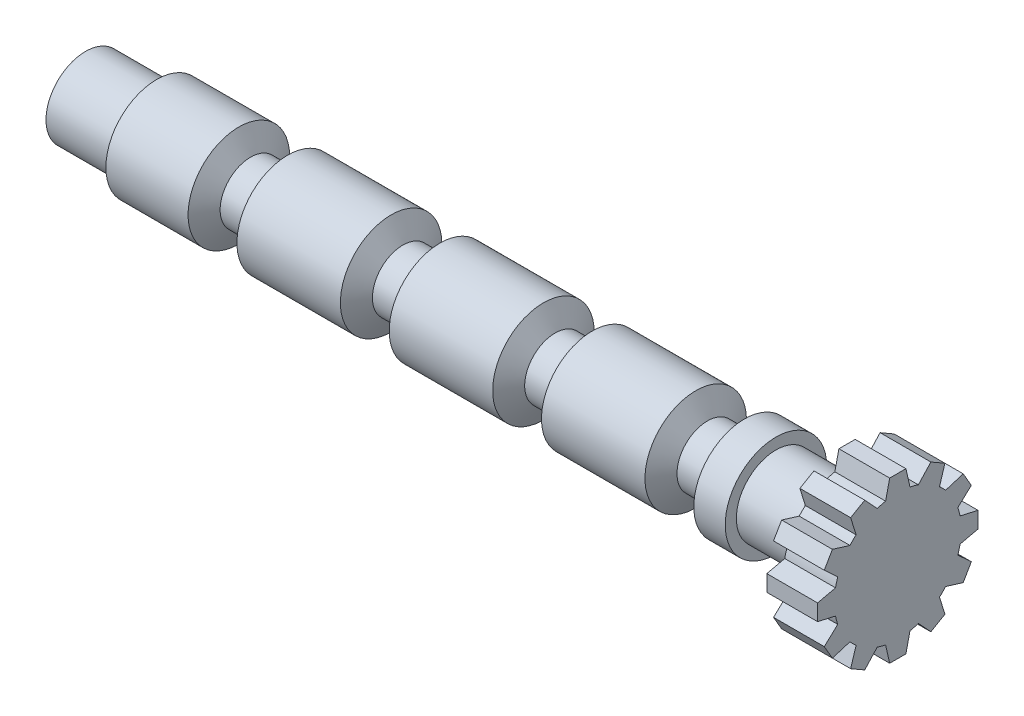
SolidWorks part; units mm, degrees
ref_plane "Front Plane" through (0, 0, 0) normal (0, 0, 1) x (1, 0, 0)
ref_plane "Top Plane" through (0, 0, 0) normal (0, 1, 0) x (1, 0, 0)
ref_plane "Right Plane" through (0, 0, 0) normal (1, 0, 0) x (0, 0, -1)
sketch "Sketch2" plane through (0, 0, 0) normal (0, 1, 0) x (1, 0, 0)
  line L1 (40, -5) -> (-40, -5)
  line L5 (-30.0491, 0) -> (-24.9047, 0)
  line L6 (-5.0953, 0) -> (-6.25, -2)
  line L7 (-6.25, -2) -> (-8.75, -2)
  line L8 (-8.75, -2) -> (-9.9047, 0)
  line L9 (-20.0953, 0) -> (-21.25, -2)
  line L10 (-21.25, -2) -> (-23.75, -2)
  line L11 (-23.75, -2) -> (-24.9047, 0)
  line L21 (-5.0953, 0) -> (5.0953, 0)
  line L22 (-20.0953, 0) -> (-9.9047, 0)
  line L25 (-30.0491, 0) -> (-40, 0)
  line L30 (-40, 0) -> (-40, -5)
  line L31 (0, 0) -> (0, -5) construction
  line L32 (40, 0) -> (40, -5)
  line L33 (30.0491, 0) -> (40, 0)
  line L34 (20.0953, 0) -> (9.9047, 0)
  line L35 (23.75, -2) -> (24.9047, 0)
  line L36 (21.25, -2) -> (23.75, -2)
  line L37 (20.0953, 0) -> (21.25, -2)
  line L38 (8.75, -2) -> (9.9047, 0)
  line L39 (6.25, -2) -> (8.75, -2)
  line L40 (5.0953, 0) -> (6.25, -2)
  line L41 (30.0491, 0) -> (24.9047, 0)
  point P2 (-7.5, -2)
  point P6 (-22.5, -2)
  dimension "D2" = 5
  dimension "D3" = 3
  dimension "D4" = 120
  dimension "D5" = 120
  dimension "D6" = 7.5
  dimension "D7" = 2.5
  dimension "D8" = 22.5
  dimension "D9" = 120
  dimension "D10" = 120
  dimension "D11" = 2.5
  dimension "D12" = 40
revolve "Revolve1" add sketch "Sketch2" angle 360 about L1
sketch "Sketch3" plane through (40, 0, 0) normal (1, 0, 0) x (0, 0, -1)
  circle A0 centre (-5, 0) radius 3.9
  circle A2 centre (-5, 0) radius 5
  circle A3 centre (-5, 0) radius 5
  dimension "D2" = 0
  dimension "D1" = 7.8
sketch "Sketch4" plane through (-40, 0, 0) normal (-1, 0, 0) x (0, 0, 1)
  circle A0 centre (5, 0) radius 3.9
  circle A2 centre (5, 0) radius 5
  circle A3 centre (5, 0) radius 5
  dimension "D1" = 7.8
  dimension "D2" = 0
extrude "Cut-Extrude2" cut sketch "Sketch4" against normal blind 7
extrude "Cut-Extrude4" cut sketch "Sketch3" against normal blind 12
sketch "Sketch6" plane through (40, 0, 0) normal (1, 0, 0) x (0, 0, -1)
  line L0 (-5, -7.9) -> (-5, 7.9) construction
  line L1 (-5.8, 7.9) -> (-4.2, 7.9)
  line L2 (-5.8, 7.9) -> (-6.3, 5.7)
  line L3 (-6.3, 5.7) -> (-3.7, 5.7)
  line L4 (-3.7, 5.7) -> (-4.2, 7.9)
  point P3 (-5, 0)
  point P4 (-5, 5.7)
  point P6 (-5, 7.9)
  point P9 (0, 0)
  point P11 (0, 0)
  point P12 (0, 0)
  dimension "D1" = 7.9
  dimension "D2" = 2.6
  dimension "D3" = 1.6
  dimension "D4" = 5.7
sketch "Sketch7" plane through (40, 0, 0) normal (1, 0, 0) x (0, 0, -1)
  circle A0 centre (-5, 0) radius 6.25
  dimension "D1" = 12.5
extrude "Boss-Extrude1" add sketch "Sketch7" against normal blind 5
extrude "Boss-Extrude2" add sketch "Sketch6" against normal blind 5
pattern_circular "CirPattern1" count 12 every 30 about axis through (0, 0, 5) along (1, 0, 0) of "Boss-Extrude2"
